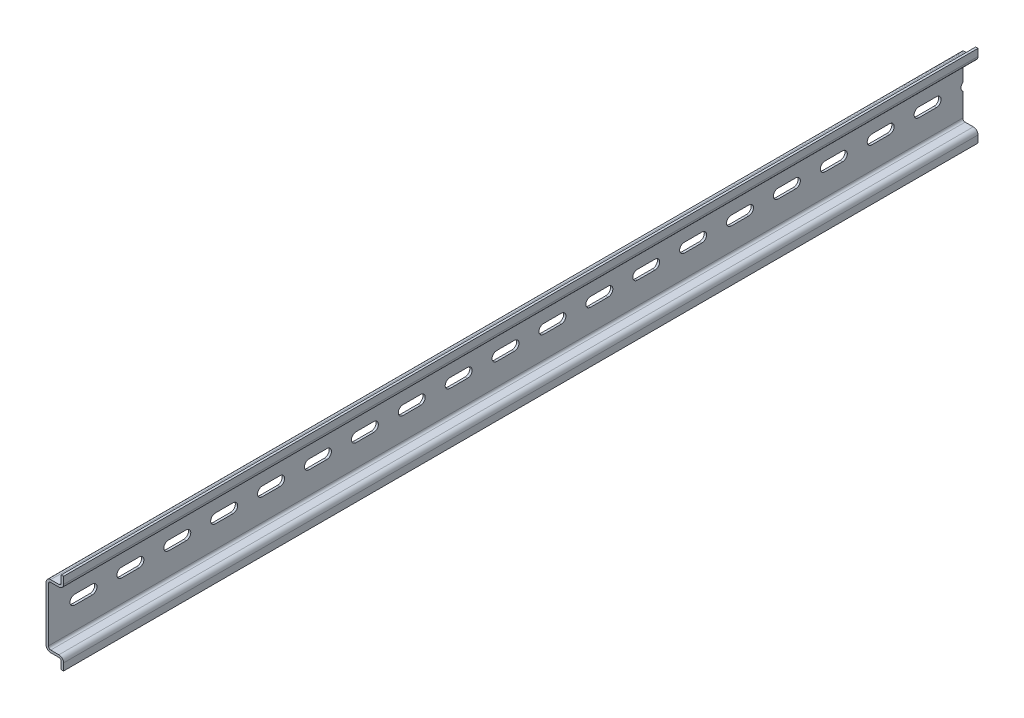
SolidWorks part; units mm, degrees
ref_plane "前视基准面" through (0, 0, 0) normal (0, 0, 1) x (1, 0, 0)
ref_plane "上视基准面" through (0, 0, 0) normal (0, 1, 0) x (1, 0, 0)
ref_plane "右视基准面" through (0, 0, 0) normal (1, 0, 0) x (0, 0, -1)
sketch "草图1" plane through (0, 0, 0) normal (0, 0, 1) x (1, 0, 0)
  line L0 (0, 19.2189) -> (1, 19.2189)
  line L1 (0, -15.7811) -> (1, -15.7811)
  line L2 (-6.5, 13.2189) -> (-6.5, -9.7811)
  line L3 (1, 19.2189) -> (1, 16.2189)
  line L4 (1, -12.7811) -> (1, -15.7811)
  line L5 (-4.5, 15.2189) -> (-1, 15.2189)
  line L6 (-4.5, -11.7811) -> (-1, -11.7811)
  line L7 (0, 19.2189) -> (0, 16.2189)
  line L8 (0, -12.7811) -> (0, -15.7811)
  line L9 (-4.5, 14.2189) -> (-1, 14.2189)
  line L10 (-4.5, -10.7811) -> (-1, -10.7811)
  line L11 (-5.5, 13.2189) -> (-5.5, -9.7811)
  arc A0 (-1, 15.2189) -> (0, 16.2189) centre (-1, 16.2189) ccw
  arc A1 (-1, 14.2189) -> (1, 16.2189) centre (-1, 16.2189) ccw
  arc A2 (0, -12.7811) -> (-1, -11.7811) centre (-1, -12.7811) ccw
  arc A3 (1, -12.7811) -> (-1, -10.7811) centre (-1, -12.7811) ccw
  arc A4 (-4.5, 14.2189) -> (-5.5, 13.2189) centre (-4.5, 13.2189) ccw
  arc A5 (-4.5, 15.2189) -> (-6.5, 13.2189) centre (-4.5, 13.2189) ccw
  arc A6 (-5.5, -9.7811) -> (-4.5, -10.7811) centre (-4.5, -9.7811) ccw
  arc A7 (-6.5, -9.7811) -> (-4.5, -11.7811) centre (-4.5, -9.7811) ccw
extrude "凸台-拉伸1" add sketch "草图1" along normal mid plane 390
sketch "草图2" plane through (-5.5, 0, 0) normal (1, 0, 0) x (0, 0, -1)
  line L0 (-195, 1.7189) -> (195, 1.7189) construction
  line L1 (-195, -9.7811) -> (-195, 13.2189) construction
  line L2 (195, -9.7811) -> (195, 13.2189) construction
  line L3 (-183.75, 1.7189) -> (-176.25, 1.7189) construction
  line L4 (-183.75, 3.7189) -> (-176.25, 3.7189)
  line L5 (-183.75, -0.2811) -> (-176.25, -0.2811)
  arc A0 (-183.75, 3.7189) -> (-183.75, -0.2811) centre (-183.75, 1.7189) ccw
  arc A1 (-176.25, -0.2811) -> (-176.25, 3.7189) centre (-176.25, 1.7189) ccw
  point P8 (-180, 1.7189)
  dimension "D1" = 7.5
  dimension "D2" = 4
  dimension "D3" = 15
extrude "切除-拉伸1" cut sketch "草图2" against normal blind 10
pattern_linear "阵列(线性)1" count 50 spacing 20 along (0, 0, -1) of "切除-拉伸1"
